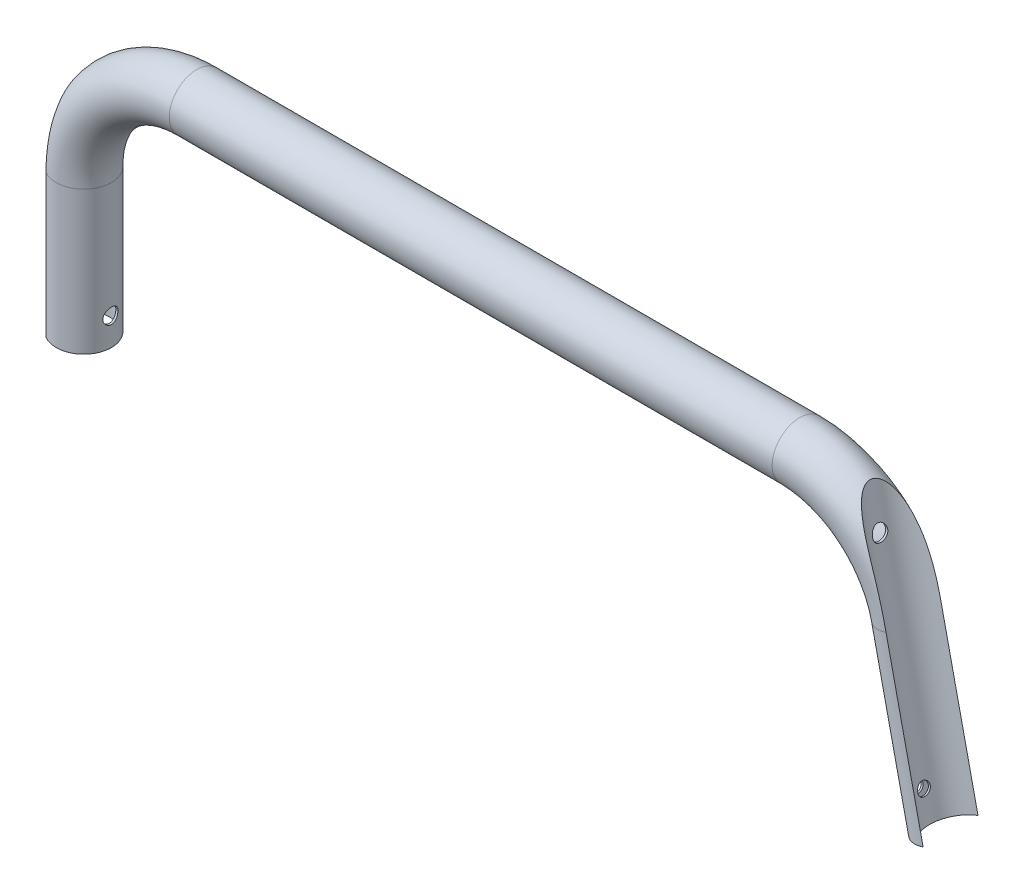
SolidWorks part; units mm, degrees
ref_plane "Front Plane" through (0, 0, 0) normal (0, 0, 1) x (1, 0, 0)
ref_plane "Top Plane" through (0, 0, 0) normal (0, 1, 0) x (1, 0, 0)
ref_plane "Right Plane" through (0, 0, 0) normal (1, 0, 0) x (0, 0, -1)
sketch "Sketch1" plane through (0, 0, 0) normal (0, 0, 1) x (1, 0, 0)
  line L1 (0, 0) -> (0, -80) construction
  line L3 (-201.5134, -101.9) -> (-201.5134, -45)
  line L5 (142.1936, -101.9) -> (127.4199, -35.2602)
  line L7 (-156.5134, 0) -> (83.4866, 0)
  arc A0 (127.4199, -35.2602) -> (83.4866, 0) centre (83.4866, -45) ccw
  arc A1 (-156.5134, 0) -> (-201.5134, -45) centre (-156.5134, -45) ccw
  point P4 (0, 0)
  point P11 (0, -80)
  dimension "D5" = 45
  dimension "D1" = 240
  dimension "D2" = 101.9
  dimension "D3" = 12.5
  dimension "D6" = 101.9
ref_plane "Plane1" through (-201.5134, -101.9, 0) normal (0, -1, 0) x (-1, 0, 0)
sketch "Sketch2" plane through (-201.5134, -101.9, 0) normal (0, -1, 0) x (-1, 0, 0)
  line L0 (-45, 0) -> (0, 0) construction
  circle A0 centre (0, 0) radius 11
  circle A1 centre (0, 0) radius 10.2
  dimension "D1" = 0.8
sweep "Sweep1" add profiles "Sketch2" path "Sketch1"
sketch "Sketch3" plane through (28.1936, -127.1732, 0) normal (0.2164, -0.9763, 0) x (0.9763, 0.2164, 0)
  line L0 (116.7679, 0) -> (120.7679, 0) construction
  circle A0 centre (120.7679, 0) radius 11.2358
  dimension "D2" = 22.4716
  dimension "D1" = 4
extrude "Cut-Extrude1" cut sketch "Sketch3" against normal through all
sketch "Sketch6" plane through (28.1936, -127.1732, 0) normal (0.2164, -0.9763, 0) x (0.9763, 0.2164, 0)
  line L0 (116.7679, 0) -> (120.7679, 0) construction
  arc A0 (131.939, 1.2036) -> (131.939, -1.2036) centre (120.7679, 0) ccw
  arc A2 (129.6119, 8.1636) -> (129.6119, -8.1636) centre (120.7679, 0) ccw
  arc A3 (129.6119, -8.1636) -> (131.939, -1.2036) centre (116.7679, 0) ccw
  circle A4 centre (120.7679, 0) radius 12.0358 construction
  circle A5 centre (120.7679, 0) radius 11.2358 construction
  arc A6 (131.939, 1.2036) -> (129.6119, 8.1636) centre (116.7679, 0) ccw
  dimension "D1" = 0.8
extrude "Boss-Extrude1" add sketch "Sketch6" against normal up to next
sketch "Sketch7" plane through (28.1936, -127.1732, 0) normal (0.2164, -0.9763, 0) x (0.9763, 0.2164, 0)
  line L0 (105.7679, 0) -> (116.7679, 0)
  arc A0 (118.1124, 10.9175) -> (118.1124, -10.9175) centre (116.7679, 0) ccw construction
ref_plane "Plane2" through (142.1936, -101.9, 0) normal (0.9763, 0.2164, 0) x (0, 0, -1)
sketch "Sketch8" plane through (142.1936, -101.9, 0) normal (0.9763, 0.2164, 0) x (0, 0, -1)
  line L0 (0, 0.0022) -> (0, 11.4022) construction
  circle A0 centre (0, 11.4022) radius 2.5
  dimension "D1" = 11.4
extrude "Cut-Extrude2" cut sketch "Sketch8" against normal up to surface (11 mm away)
ref_plane "Plane3" through (180, 0, 0) normal (1, 0, 0) x (0, 0, -1)
sketch "Sketch9" plane through (180, 0, 0) normal (1, 0, 0) x (0, 0, -1)
  circle A0 centre (0, -12.919) radius 3
extrude "Cut-Extrude3" cut sketch "Sketch9" against normal up to next
sketch "Sketch10" plane through (0, -101.9, 0) normal (0, -1, 0) x (1, 0, 0)
  line L1 (-201.5134, 0) -> (-201.5134, 11) construction
  line L2 (-201.5134, 0) -> (-215.5134, 0) construction
  circle A0 centre (-201.5134, 0) radius 11 construction
  circle A2 centre (-215.5134, 0) radius 12.7
  dimension "D1" = 14
extrude "Cut-Extrude4" cut sketch "Sketch10" against normal up to next
sketch "Sketch11" plane through (0, -101.9, 0) normal (0, -1, 0) x (1, 0, 0)
  arc A0 (-207.0745, 9.4908) -> (-207.0745, -9.4908) centre (-215.5134, 0) cw
  arc A5 (-206.1316, 9.9836) -> (-206.1316, -9.9836) centre (-215.5134, 0) cw
  arc A6 (-207.0745, -9.4908) -> (-206.1316, -9.9836) centre (-201.5134, 0) ccw
  arc A7 (-206.41, 10.2381) -> (-206.41, -10.2381) centre (-215.5134, 0) cw construction
  arc A8 (-206.1316, 9.9836) -> (-207.0745, 9.4908) centre (-201.5134, 0) ccw
  dimension "D1" = 1
extrude "Boss-Extrude2" add sketch "Sketch11" against normal up to next
ref_plane "Plane5" through (-190.5134, 0, 0) normal (1, 0, 0) x (0, 0, -1)
sketch "Sketch13" plane through (-190.5134, 0, 0) normal (1, 0, 0) x (0, 0, -1)
  line L0 (-11, -101.9) -> (11, -101.9) construction
  circle A0 centre (0, -90.9) radius 3
  point P4 (0, -101.9)
  dimension "D1" = 11
  dimension "D2" = 6
extrude "Cut-Extrude5" cut sketch "Sketch13" against normal through all
